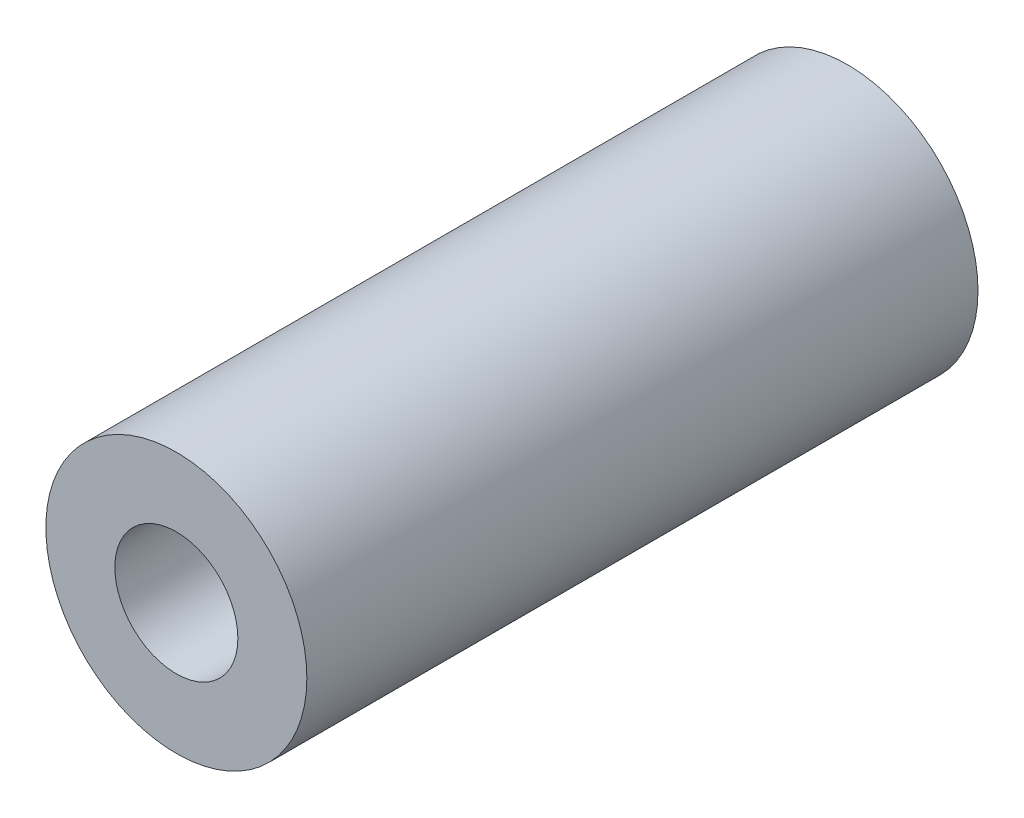
SolidWorks part; units mm, degrees
ref_plane "Front Plane" through (0, 0, 0) normal (1, 0, 0) x (0, 1, 0)
ref_plane "Top Plane" through (0, 0, 0) normal (0, 0, 1) x (0, 1, 0)
ref_plane "Right Plane" through (0, 0, 0) normal (0, 1, 0) x (-1, 0, 0)
sketch "Sketch1" plane through (0, 0, 0) normal (0, 0, 1) x (0, 1, 0)
  circle A0 centre (0, 0) radius 3.5
  circle A1 centre (0, 0) radius 1.65
  dimension "D1" = 3.3
  dimension "D2" = 7
extrude "Boss-Extrude1" add sketch "Sketch1" along normal blind 18
